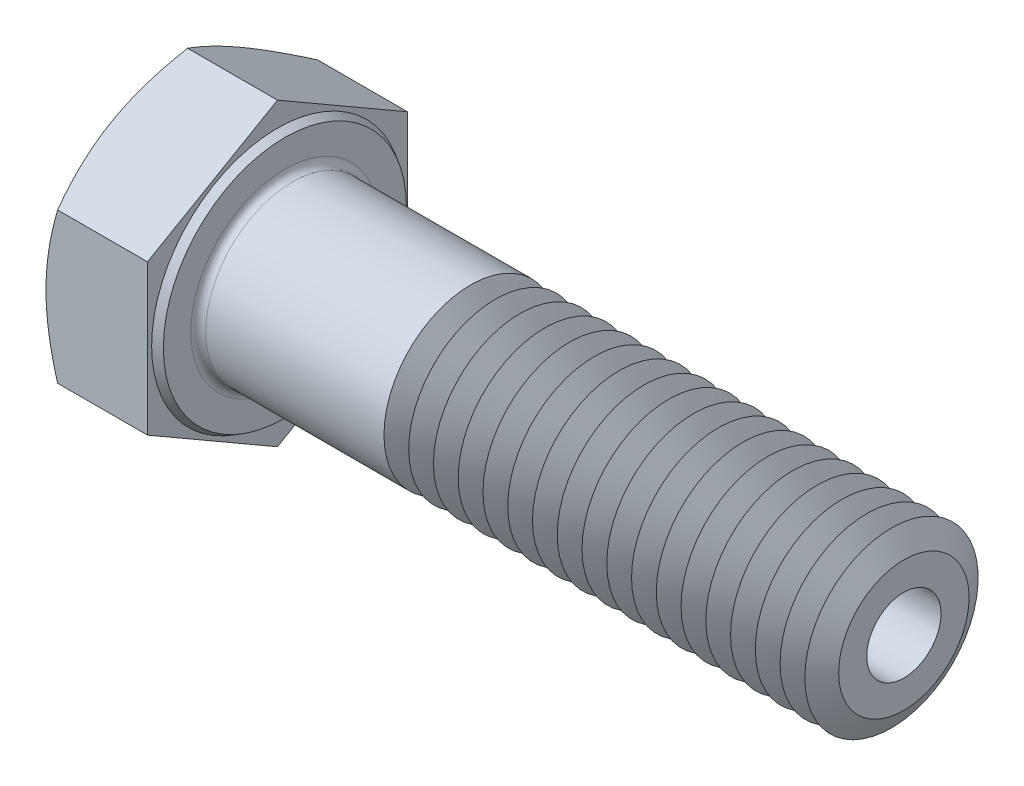
SolidWorks part; units mm, degrees
material "45"
ref_plane "前视" through (0, 0, 0) normal (0, 0, 1) x (1, 0, 0)
ref_plane "上视" through (0, 0, 0) normal (0, 1, 0) x (1, 0, 0)
ref_plane "右视" through (0, 0, 0) normal (1, 0, 0) x (0, 0, -1)
sketch "草图1" plane through (0, 0, 0) normal (1, 0, 0) x (0, 0, -1)
  line L0 (10.5, 6.0622) -> (10.5, -6.0622)
  line L1 (-10.5, 6.0622) -> (-10.5, -6.0622)
  line L2 (10.5, -6.0622) -> (0, -12.1244)
  line L3 (0, -12.1244) -> (-10.5, -6.0622)
  line L4 (10.5, 6.0622) -> (0, 12.1244)
  line L5 (0, 12.1244) -> (-10.5, 6.0622)
  circle A0 centre (0, 0) radius 11.68 construction
  dimension "e" = 23.36
  dimension "s" = 21
  dimension "D2" = 120
  dimension "D3" = 10.5
  dimension "D4" = 10.5
  dimension "D5" = 10.5
extrude "基体-拉伸" add sketch "草图1" along normal blind 8.8
sketch "草图2" plane through (0, 0, 0) normal (0, 0, 1) x (1, 0, 0)
  line L0 (0, 6.0622) -> (0, -6.0622) construction
  line L1 (0, 0) -> (58.8, 0)
  line L2 (0, 0) -> (0, 7)
  line L3 (0, 7) -> (58.8, 7)
  line L4 (58.8, 0) -> (58.8, 5.268)
  line L5 (8.8, 12.1244) -> (8.8, 6.0622) construction
  line L6 (0, 0) -> (-15.7, 0) construction
  line L7 (0, 0) -> (29.4, 0) construction
  line L8 (58.8, -5.268) -> (90.335, -7) construction
  line L9 (0, -7) -> (90.335, -7) construction
  line L10 (10.8, 7) -> (10.8, 0) construction
  line L11 (8.8, 13.0554) -> (8.8, -1.27) construction
  line L12 (8.8, 6.0622) -> (8.8, -6.0622) construction
  line L14 (58.8, 7) -> (58.8, 5.268)
  dimension "l" = 50
  dimension "d" = 14
  dimension "Minor_dia" = 10.536
  dimension "p" = 2
  dimension "b" = 50
  dimension "da" = 15.7
revolve "凸台-旋转1" add sketch "草图2" angle 360 about L7
cosmetic thread "螺旋线1" parameters "Thread_length"=13, "Thread_minor"=10.536
sketch "草图3" plane through (0, 0, 0) normal (0, 0, 1) x (1, 0, 0)
  line L0 (0, 10.5) -> (3.8246, 17.1244)
  line L1 (0, 12.1244) -> (0, 6.0622) construction
  line L2 (3.8246, 17.1244) -> (3.8246, 22.1244)
  line L3 (3.8246, 22.1244) -> (-10, 22.1244)
  line L4 (-10, 22.1244) -> (-10, 10.5)
  line L5 (-10, 10.5) -> (0, 10.5)
  line L6 (0, 0) -> (99.06, 0) construction
  line L7 (8.8, 12.1244) -> (0, 12.1244) construction
  dimension "D1" = 10.5
  dimension "D2" = 5
  dimension "D3" = 10
  dimension "D4" = 5
  dimension "Head_ch_ang" = 30
revolve "切除-旋转1" cut sketch "草图3" angle 360 about L6
sketch "草图4" plane through (0, 0, 0) normal (0, 0, 1) x (1, 0, 0)
  line L0 (0, 0) -> (248.9073, 0) construction
  line L2 (8.8, 0) -> (8.8, 9.82) construction
  line L3 (8.8, -7) -> (8.8, 7) construction
  line L4 (8.8, 12.1244) -> (8.8, 6.0622) construction
  line L9 (8.8, 9.82) -> (8.2, 10.1664)
  line L10 (8.2, 10.1664) -> (8.2, 12.1244)
  line L11 (8.8, 12.1244) -> (0.9378, 12.1244) construction
  line L12 (8.2, 12.1244) -> (8.8, 12.1244)
  line L13 (8.8, 12.1244) -> (8.8, 9.82)
  dimension "D1" = 120
  dimension "c" = 0.6
  dimension "dw" = 19.64
revolve "切除-旋转3" cut sketch "草图4" angle 360 about L0
fillet "圆角" radius 0.6 1 edges at (8.8, 0, -7)
sketch "草图6" plane through (0, 0, 0) normal (0, 0, 1) x (1, 0, 0)
  line L0 (0, 0) -> (58.8, 0) construction
  line L1 (58.8, -7) -> (58.8, 7) construction
  line L2 (58.8, 0) -> (58.8, 7) construction
  line L4 (57.8, 7) -> (59.8, 7)
  line L5 (57.8, 7) -> (58.8, 5.2679)
  line L6 (58.8, 5.2679) -> (59.8, 7)
  dimension "D1" = 2
revolve "切除-旋转4" cut sketch "草图6" angle 360 about L0
pattern_linear "阵列(线性)1" count 18 spacing 2 along (-1, 0, 0) of "切除-旋转4"
hole_wizard "Ø6.0 (6) 直径孔1" positions "3D草图1" profile "草图7" hole size "Ø6.0" standard "GB" end condition through all
sketch3d "3D草图1"
  arc A0 (0, 0, 10.5) -> (0, -9.0933, 5.25) centre (0, 0, 0) ccw construction
  point P0 (0, 0, 0)
  point P6 (10.5, 0, 0)
sketch "草图7" plane through (0, 0, 0) normal (0, 1, 0) x (0, 0, 1)
  line L0 (0, 0) -> (0, 58.8)
  line L1 (0, 58.8) -> (3, 58.8)
  line L2 (3, 58.8) -> (3, 0)
  line L5 (3, 0) -> (0, 0)
  line L11 (0, -6.35) -> (0, 107.95) construction
  dimension "通孔孔直径" = 6
  dimension "通孔孔深度" = 58.8
hole_wizard "M8x1.0 螺纹孔1" positions "3D草图2" profile "草图8" tap size "M8x1.0" standard "GB"
sketch3d "3D草图2"
  arc A0 (0, 0, 10.5) -> (0, -9.0933, 5.25) centre (0, 0, 0) ccw construction
  point P0 (0, 0, 0)
  point P6 (10.5, 0, 0)
sketch "草图8" plane through (0, 0, 0) normal (0, 1, 0) x (0, 0, 1)
  line L0 (0, 0) -> (0, 15.103)
  line L1 (0, 15.103) -> (3.5, 13)
  line L2 (3.5, 13) -> (3.5, 0)
  line L5 (3.5, 0) -> (0, 0)
  line L10 (0, 15.103) -> (-3.5, 13) construction
  line L11 (0, -6.35) -> (0, 107.95) construction
  dimension "螺纹孔钻头直径" = 7
  dimension "螺纹孔钻头深度" = 13
  dimension "导头角度" = 118
cosmetic thread "孔螺蚊线1" parameters "D1"=10, "D2"=8
